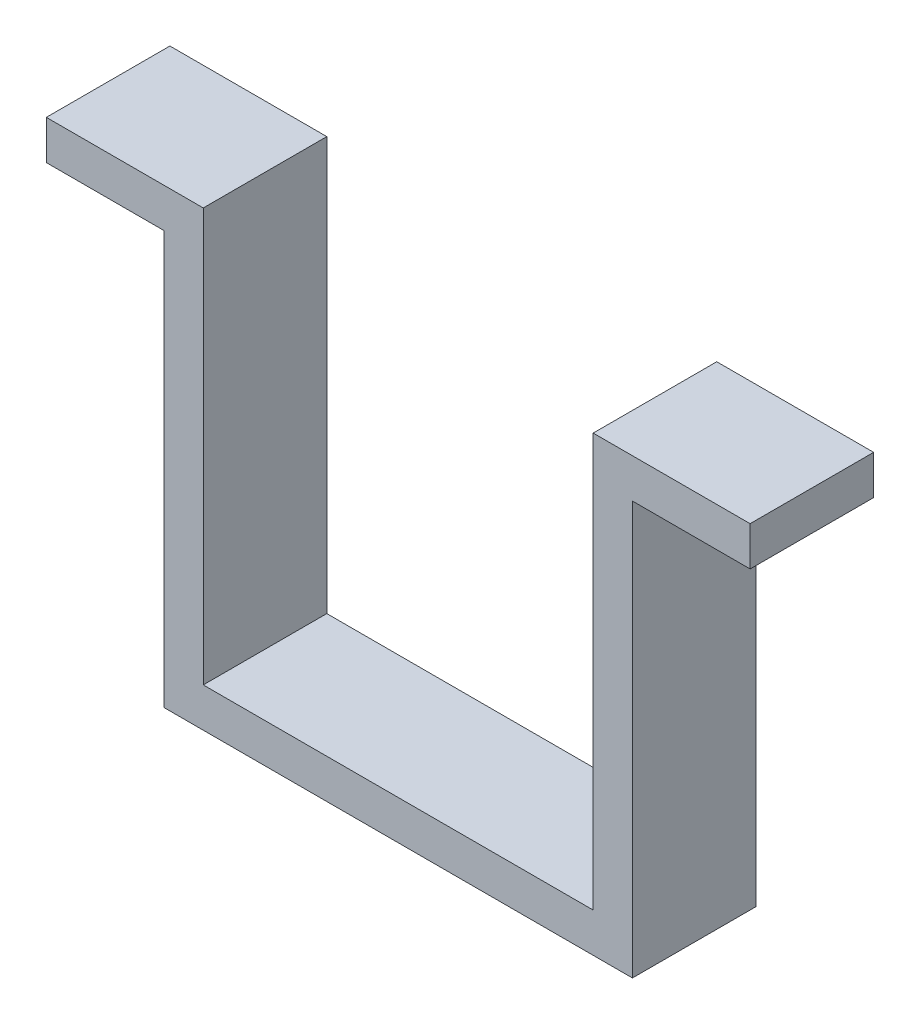
SolidWorks part; units mm, degrees
ref_plane "Front Plane" through (0, 0, 0) normal (0, 0, 1) x (1, 0, 0)
ref_plane "Top Plane" through (0, 0, 0) normal (0, 1, 0) x (1, 0, 0)
ref_plane "Right Plane" through (0, 0, 0) normal (1, 0, 0) x (0, 0, -1)
sketch "Sketch1" plane through (0, 0, 0) normal (0, 0, 1) x (1, 0, 0)
  line L0 (0, 90.3736) -> (0, -84.4624) construction
  line L1 (-135.9551, 0) -> (167.1128, 0) construction
  line L2 (-18.955, 13.5415) -> (-18.955, -19.8915)
  line L3 (-18.955, 13.5415) -> (-18.955, 13.5415) construction
  line L4 (-15.78, -16.7165) -> (0, -16.7165)
  line L5 (-15.78, 16.7165) -> (-28.48, 16.7165)
  line L6 (-18.955, -19.8915) -> (0, -19.8915)
  line L7 (-15.78, 16.7165) -> (-15.78, 60.7317) construction
  line L8 (-15.78, 16.7165) -> (-15.78, -16.7165)
  line L9 (-18.955, 13.5415) -> (-28.48, 13.5415)
  line L10 (-28.48, 16.7165) -> (-28.48, 13.5415)
  line L11 (-15.78, 60.7317) -> (-15.78, -16.7165) construction
  line L12 (-18.955, 13.5415) -> (-18.955, -19.8915) construction
  line L13 (15.78, -16.7165) -> (0, -16.7165)
  line L14 (18.955, -19.8915) -> (0, -19.8915)
  line L15 (18.955, 13.5415) -> (18.955, -19.8915)
  line L16 (15.78, 16.7165) -> (15.78, -16.7165)
  line L17 (18.955, 13.5415) -> (28.48, 13.5415)
  line L18 (28.48, 16.7165) -> (28.48, 13.5415)
  line L19 (15.78, 16.7165) -> (28.48, 16.7165)
  point P10 (-15.78, 0)
  dimension "D2" = 30.258
  dimension "D1" = 3.175
  dimension "D3" = 15.78
  dimension "D4" = 12.7
extrude "Boss-Extrude1" add sketch "Sketch1" along normal blind 10 contours L8 L4 L13 L16 L19 L18 L17 L15 L14 L6 L2 L9 L10 L5
